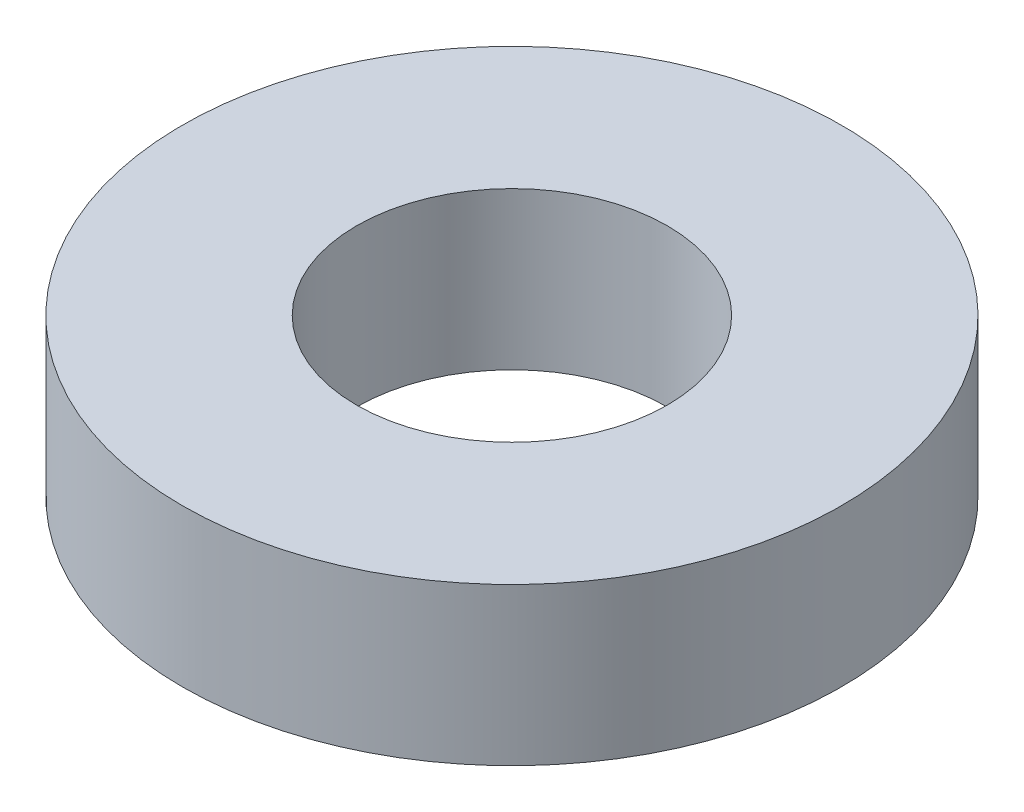
SolidWorks part; units mm, degrees
material "Galvanized Steel"
ref_plane "Front Plane" through (0, 0, 0) normal (0, 0, 1) x (1, 0, 0)
ref_plane "Top Plane" through (0, 0, 0) normal (0, 1, 0) x (1, 0, 0)
ref_plane "Right Plane" through (0, 0, 0) normal (1, 0, 0) x (0, 0, -1)
sketch "Sketch1" plane through (0, 0, 0) normal (0, 1, 0) x (1, 0, 0)
  circle A0 centre (0, 0) radius 10.5
  circle A1 centre (0, 0) radius 4.95
  dimension "D1" = 21
  dimension "D2" = 9.9
extrude "Boss-Extrude1" add sketch "Sketch1" along normal blind 5
